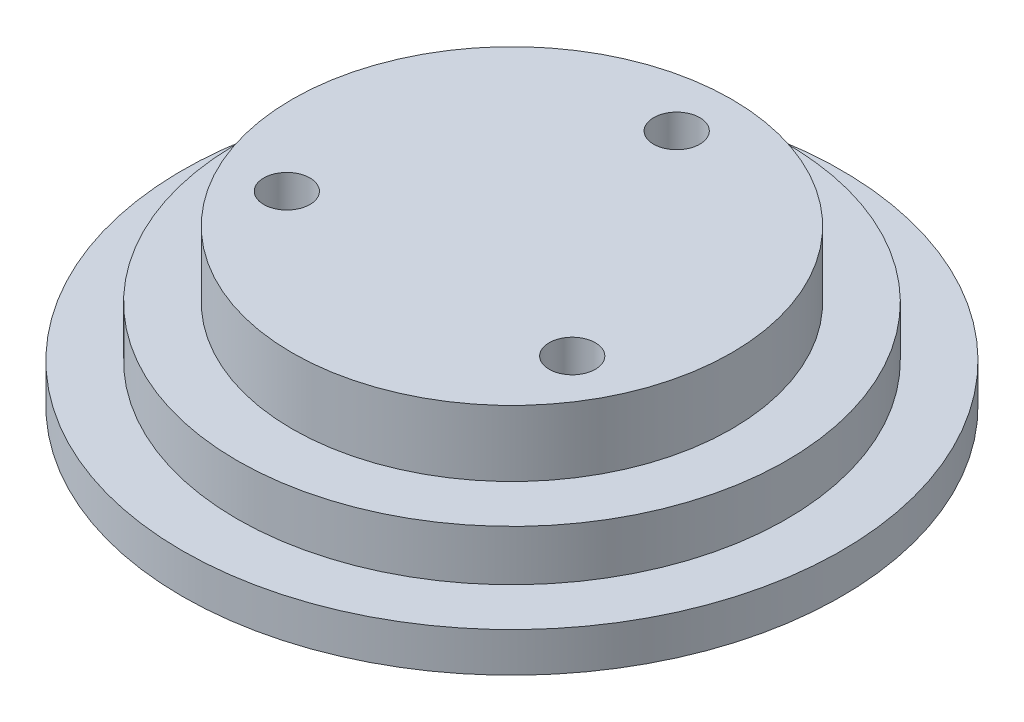
SolidWorks part; units mm, degrees
ref_plane "Front Plane" through (0, 0, 0) normal (0, 0, 1) x (1, 0, 0)
ref_plane "Top Plane" through (0, 0, 0) normal (0, 1, 0) x (1, 0, 0)
ref_plane "Right Plane" through (0, 0, 0) normal (1, 0, 0) x (0, 0, -1)
sketch "Sketch1" plane through (0, 0, 0) normal (0, 1, 0) x (1, 0, 0)
  circle A0 centre (0, 0) radius 30
  dimension "D1" = 60
extrude "Boss-Extrude1" add sketch "Sketch1" along normal blind 3.6
sketch "Sketch2" plane through (0, 3.6, 0) normal (0, 1, 0) x (1, 0, 0)
  circle A0 centre (0, 0) radius 25
  dimension "D1" = 50
extrude "Boss-Extrude2" add sketch "Sketch2" along normal blind 4.6
sketch "Sketch3" plane through (0, 8.2, 0) normal (0, 1, 0) x (1, 0, 0)
  circle A0 centre (0, 0) radius 20
  dimension "D1" = 40
extrude "Boss-Extrude3" add sketch "Sketch3" along normal blind 6
sketch "Sketch4" plane through (0, 14.2, 0) normal (0, 1, 0) x (1, 0, 0)
  line L0 (0, 20) -> (0, 0) construction
  line L1 (0, 0) -> (-17.3205, -10) construction
  line L2 (0, 0) -> (17.3205, -10) construction
  circle A0 centre (0, 0) radius 20 construction
  circle A1 centre (0, 0) radius 20 construction
  circle A2 centre (0, 15) radius 2.1
  circle A3 centre (12.9904, -7.5) radius 2.1
  circle A4 centre (-12.9904, -7.5) radius 2.1
  circle A5 centre (0, 0) radius 15 construction
  dimension "D1" = 4.2
  dimension "D2" = 30
  dimension "D5" = 120
  dimension "D6" = 120
extrude "Cut-Extrude1" cut sketch "Sketch4" against normal up to next
chamfer "Chamfer1" distance 2 angle 45 3 edges at (-12.9904, 0, 9.6) (12.9904, 0, 9.6) (0, 0, -12.9)
